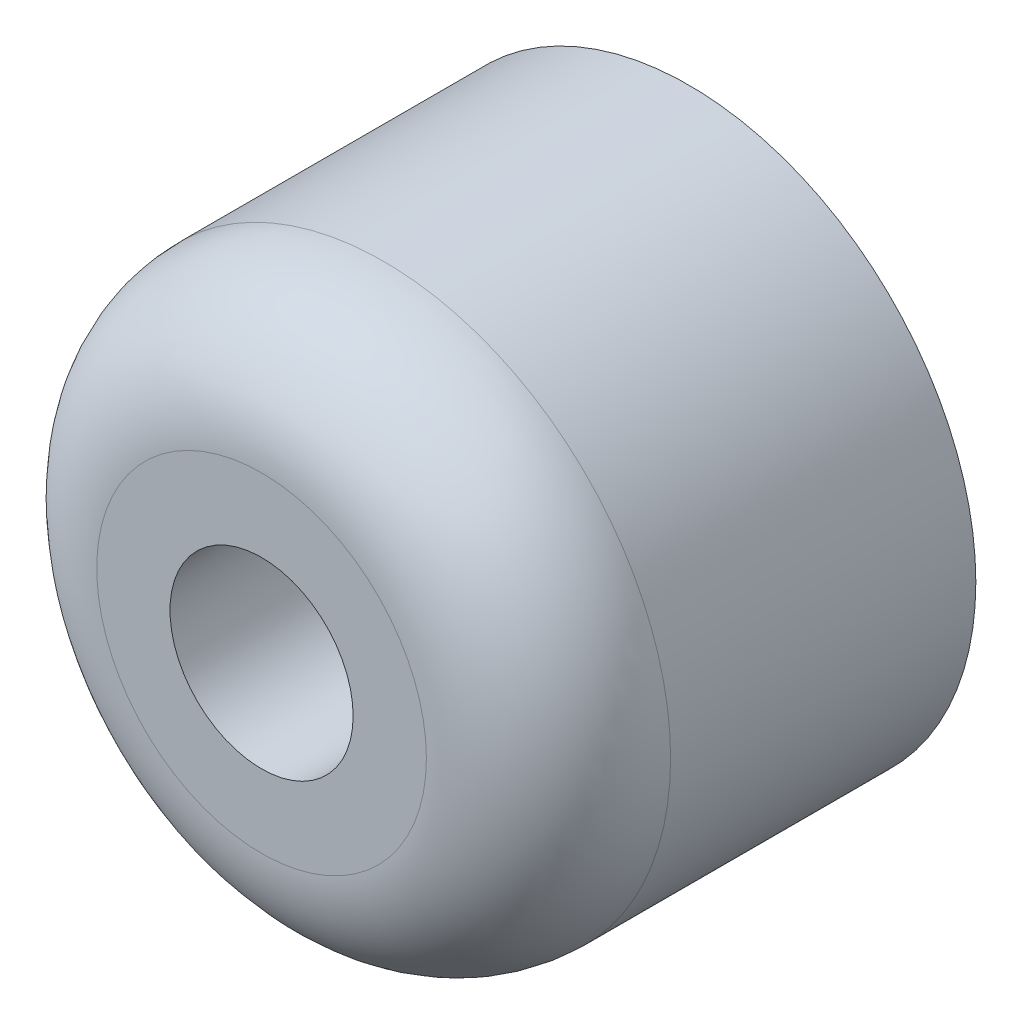
SolidWorks part; units mm, degrees
ref_plane "Спереди" through (0, 0, 0) normal (0, 0, 1) x (1, 0, 0)
ref_plane "Сверху" through (0, 0, 0) normal (0, 1, 0) x (1, 0, 0)
ref_plane "Справа" through (0, 0, 0) normal (1, 0, 0) x (0, 0, -1)
other "Configuration Table"
sketch "Эскиз2" plane through (0, 0, 0) normal (0, 0, 1) x (1, 0, 0)
  circle A0 centre (0, 0) radius 23.5
  dimension "D1" = 47
extrude "Бобышка-Вытянуть1" add sketch "Эскиз2" along normal blind 35
fillet "Скругление3" radius 10 1 edges at (23.5, 0, 35)
shell "Оболочка2" thickness 2
sketch "Эскиз5" plane through (0, 0, 33) normal (0, 0, -1) x (-1, 0, 0)
  circle A0 centre (0, 0) radius 9.5
  dimension "D1" = 19
extrude "Бобышка-Вытянуть2" add sketch "Эскиз5" along normal blind 33
sketch "Эскиз6" plane through (0, 0, 0) normal (0, 0, -1) x (-1, 0, 0)
  circle A0 centre (0, 0) radius 2.4
  dimension "D1" = 4.8
extrude "Вырез-Вытянуть1" cut sketch "Эскиз6" against normal through all
sketch "Эскиз7" plane through (0, 0, 0) normal (0, 0, -1) x (-1, 0, 0)
  line L0 (0, 29.4416) -> (0, -31.5446) construction
  line L1 (-0.6, 8.9376) -> (-0.6, 21.9376)
  line L2 (-0.6, 21.9376) -> (0.6, 21.9376)
  line L3 (0.6, 21.9376) -> (0.6, 8.9376)
  line L4 (0.6, 8.9376) -> (-0.6, 8.9376)
  line L5 (7.4402, 4.9884) -> (18.6985, 11.4884)
  line L6 (8.0402, 3.9492) -> (7.4402, 4.9884)
  line L7 (18.6985, 11.4884) -> (19.2985, 10.4492)
  line L8 (19.2985, 10.4492) -> (8.0402, 3.9492)
  line L9 (8.0402, -3.9492) -> (19.2985, -10.4492)
  line L10 (7.4402, -4.9884) -> (8.0402, -3.9492)
  line L11 (19.2985, -10.4492) -> (18.6985, -11.4884)
  line L12 (18.6985, -11.4884) -> (7.4402, -4.9884)
  line L13 (0.6, -8.9376) -> (0.6, -21.9376)
  line L14 (-0.6, -8.9376) -> (0.6, -8.9376)
  line L15 (0.6, -21.9376) -> (-0.6, -21.9376)
  line L16 (-0.6, -21.9376) -> (-0.6, -8.9376)
  line L17 (-7.4402, -4.9884) -> (-18.6985, -11.4884)
  line L18 (-8.0402, -3.9492) -> (-7.4402, -4.9884)
  line L19 (-18.6985, -11.4884) -> (-19.2985, -10.4492)
  line L20 (-19.2985, -10.4492) -> (-8.0402, -3.9492)
  line L21 (-8.0402, 3.9492) -> (-19.2985, 10.4492)
  line L22 (-7.4402, 4.9884) -> (-8.0402, 3.9492)
  line L23 (-19.2985, 10.4492) -> (-18.6985, 11.4884)
  line L24 (-18.6985, 11.4884) -> (-7.4402, 4.9884)
  circle A0 centre (0, 0) radius 23.5 construction
  point P32 (0, 0)
  dimension "D4" = 21.9376
  dimension "D1" = 1.2
  dimension "D2" = 0.6
  dimension "D3" = 13
  dimension "D5" = 6
extrude "Бобышка-Вытянуть3" add sketch "Эскиз7" against normal up to body
sketch "Эскиз8" plane through (0, 0, 35) normal (0, 0, 1) x (1, 0, 0)
  circle A0 centre (0, 0) radius 7.5
  dimension "D1" = 15
extrude "Вырез-Вытянуть2" cut sketch "Эскиз8" against normal blind 22.5
chamfer "Фаска1" distance 3 angle 45 1 edges at (2.4, 0, 12.5)
